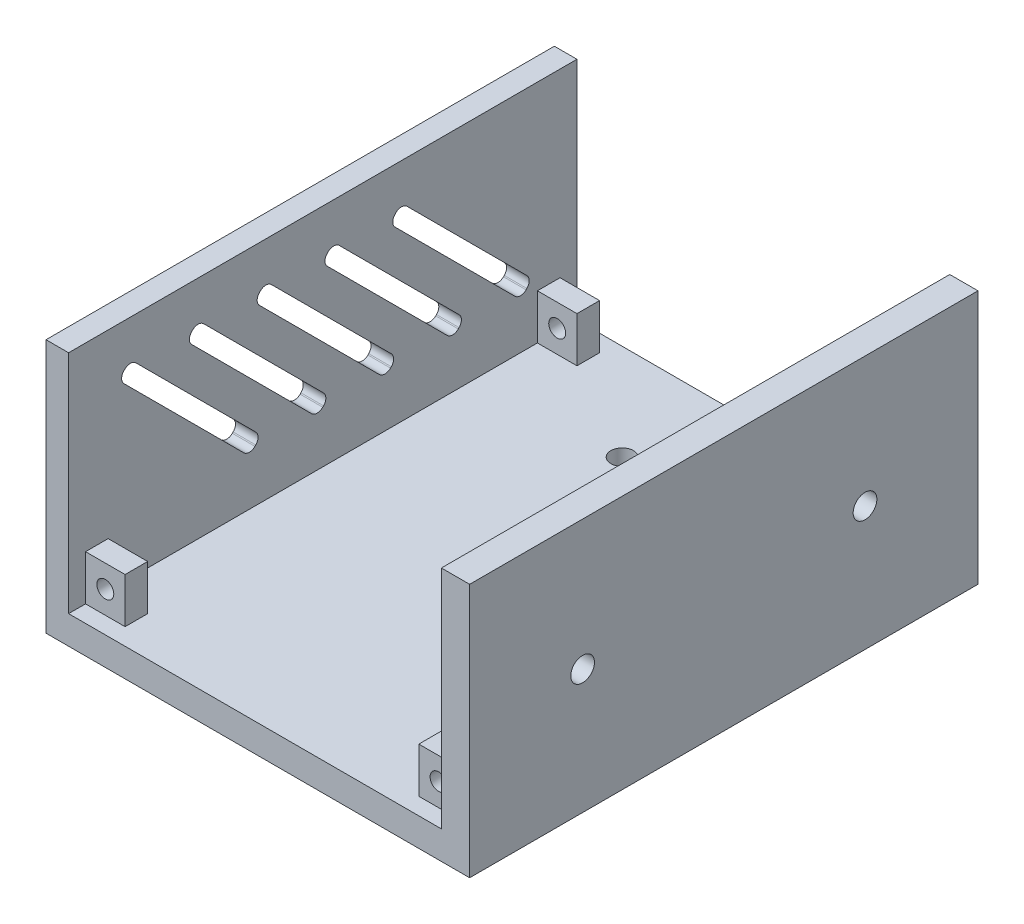
SolidWorks part; units mm, degrees
ref_plane "Front Plane" through (0, 0, 0) normal (0, 0, 1) x (1, 0, 0)
ref_plane "Top Plane" through (0, 0, 0) normal (0, 1, 0) x (1, 0, 0)
ref_plane "Right Plane" through (0, 0, 0) normal (1, 0, 0) x (0, 0, -1)
sketch "Sketch1" plane through (0, 0, 0) normal (0, 0, 1) x (1, 0, 0)
  line L1 (-37.5, -2.5) -> (37.5, -2.5)
  line L2 (-37.5, -2.5) -> (-37.5, 2.5)
  line L3 (-37.5, 2.5) -> (37.5, 2.5)
  line L4 (37.5, -2.5) -> (37.5, 2.5)
  line L5 (-37.5, -2.5) -> (37.5, 2.5) construction
  line L6 (-37.5, 2.5) -> (37.5, -2.5) construction
  line L7 (37.5, 2.5) -> (32.5, 2.5)
  line L8 (37.5, 2.5) -> (37.5, 42.5)
  line L9 (37.5, 42.5) -> (32.5, 42.5)
  line L10 (32.5, 2.5) -> (32.5, 42.5)
  point P0 (0, 0)
  dimension "D1" = 5
  dimension "D2" = 5
  dimension "D3" = 75
  dimension "D4" = 45
extrude "Boss-Extrude1" add sketch "Sketch1" along normal blind 90 contours L1 L4 L3 L2 | L10 L3 L8 L9
sketch "Sketch2" plane through (32.5, 0, 0) normal (-1, 0, 0) x (0, 0, 1)
  line L0 (0, 2.5) -> (0, 42.5) construction
  line L2 (90, 42.5) -> (0, 42.5) construction
  circle A0 centre (20, 19.5) radius 2.1
  circle A1 centre (70, 19.5) radius 2.1
  dimension "D1" = 4.2
  dimension "D2" = 4.2
  dimension "D3" = 20
  dimension "D4" = 50
  dimension "D5" = 23
extrude "Cut-Extrude1" cut sketch "Sketch2" against normal through all
sketch "Sketch4" plane through (0, 2.5, 0) normal (0, 1, 0) x (1, 0, 0)
  line L0 (-37.5, 0) -> (32.5, 0) construction
  line L1 (-37.5, -90) -> (-33.5, -90)
  line L2 (-37.5, -90) -> (-37.5, 0)
  line L3 (-37.5, 0) -> (-33.5, 0)
  line L4 (-33.5, -90) -> (-33.5, 0)
  dimension "D1" = 4
extrude "Boss-Extrude2" add sketch "Sketch4" along normal up to surface (40 mm away) up to face at (35, 42.5, 45)
sketch "Sketch6" plane through (0, 2.5, 0) normal (0, 1, 0) x (1, 0, 0)
  line L0 (-33.5, -90) -> (-33.5, 0) construction
  line L1 (-33.5, -3) -> (-26.5, -3)
  line L2 (-33.5, -3) -> (-33.5, -7)
  line L3 (-33.5, -7) -> (-26.5, -7)
  line L4 (-26.5, -3) -> (-26.5, -7)
  line L5 (-33.5, 0) -> (32.5, 0) construction
  line L6 (-33.5, -45) -> (32.5, -45) construction
  line L7 (32.5, -90) -> (32.5, 0) construction
  line L8 (-0.5, 0) -> (-0.5, -90) construction
  line L9 (-33.5, -90) -> (32.5, -90) construction
  line L10 (25.5, -3) -> (25.5, -7)
  line L11 (32.5, -7) -> (25.5, -7)
  line L12 (32.5, -3) -> (32.5, -7)
  line L13 (32.5, -3) -> (25.5, -3)
  line L14 (32.5, -87) -> (25.5, -87)
  line L15 (32.5, -87) -> (32.5, -83)
  line L16 (32.5, -83) -> (25.5, -83)
  line L17 (25.5, -87) -> (25.5, -83)
  line L18 (-26.5, -87) -> (-26.5, -83)
  line L19 (-33.5, -83) -> (-26.5, -83)
  line L20 (-33.5, -87) -> (-33.5, -83)
  line L21 (-33.5, -87) -> (-26.5, -87)
  dimension "D1" = 3
  dimension "D2" = 4
  dimension "D3" = 7
extrude "Boss-Extrude4" add sketch "Sketch6" along normal blind 8
sketch "Sketch7" plane through (0, 2.5, 0) normal (0, 1, 0) x (1, 0, 0)
  line L0 (-33.5, -90) -> (32.5, -90) construction
  line L1 (32.5, -90) -> (32.5, 0) construction
  circle A0 centre (24.5, -68) radius 1.6
  circle A1 centre (-8.5, -17) radius 1.6
  dimension "D1" = 3.2
  dimension "D4" = 3.2
  dimension "D2" = 51
  dimension "D3" = 33
  dimension "D5" = 22
  dimension "D6" = 8
extrude "Cut-Extrude3" cut sketch "Sketch7" against normal through all
sketch "Sketch8" plane through (-37.5, 0, 0) normal (-1, 0, 0) x (0, 0, 1)
  line L0 (90, -2.5) -> (0, -2.5) construction
  line L1 (32.0613, 34.9899) -> (32.2027, 34.8485)
  line L2 (30.0814, 34.9899) -> (8.8686, 13.7772)
  line L3 (8.8686, 11.7973) -> (9.0101, 11.6559)
  line L4 (32.2027, 32.8686) -> (10.9899, 11.6559)
  line L5 (90, 42.5) -> (0, 42.5) construction
  line L6 (0, -2.5) -> (0, 42.5) construction
  arc A0 (8.8686, 13.7772) -> (8.8686, 11.7973) centre (9.8586, 12.7873) ccw
  arc A1 (9.0101, 11.6559) -> (10.9899, 11.6559) centre (10, 12.6458) ccw
  arc A2 (32.2027, 34.8485) -> (32.2027, 32.8686) centre (31.2127, 33.8586) cw
  arc A3 (32.0613, 34.9899) -> (30.0814, 34.9899) centre (31.0713, 34) ccw
  point P14 (33.1926, 33.8586)
  point P17 (31.0713, 35.9799)
  dimension "D3" = 1.4
  dimension "D1" = 45
  dimension "D2" = 3
  dimension "D4" = 30
  dimension "D5" = 8.5
  dimension "D6" = 10
extrude "Cut-Extrude4" cut sketch "Sketch8" against normal up to next
pattern_linear "LPattern1" count 5 spacing 12 along (0, 0, 1) of "Cut-Extrude4"
sketch "Sketch9" plane through (0, 0, 87) normal (0, 0, 1) x (1, 0, 0)
  line L0 (-26.5, 10.5) -> (-26.5, 2.5) construction
  line L1 (-33.5, 10.5) -> (-26.5, 10.5) construction
  line L3 (25.5, 10.5) -> (25.5, 2.5) construction
  circle A0 centre (-30, 6.5) radius 1.5
  circle A1 centre (29, 6.5) radius 1.5
  dimension "D1" = 3
  dimension "D2" = 3
  dimension "D5" = 3.5
  dimension "D3" = 3.5
  dimension "D4" = 4
extrude "Cut-Extrude5" cut sketch "Sketch9" against normal through all
hole_wizard "CSK for M4 Countersunk Flat Head Screw1" positions "3DSketch1" profile "Sketch10" countersink size "M4" standard "ISO" end condition through all
sketch3d "3DSketch1"
  line L0 (24.5, -2.5, 68) -> (24.5, 2.5, 68) construction
  line L1 (-8.5, -2.5, 17) -> (-8.5, 2.5, 17) construction
  point P0 (24.5, -2.5, 68)
  point P4 (-8.5, -2.5, 17)
sketch "Sketch10" plane through (24.5, -2.5, 68) normal (1, 0, 0) x (0, 0, -1)
  line L0 (0, 0) -> (0, 45)
  line L1 (0, 45) -> (2, 45)
  line L2 (2, 45) -> (2, 1.75)
  line L3 (2, 1.75) -> (3.75, 0)
  line L5 (3.75, 0) -> (0, 0)
  line L6 (-2, 1.75) -> (-3.75, 0) construction
  line L11 (0, -6.35) -> (0, 107.95) construction
  dimension "Thru Hole Dia." = 4
  dimension "Thru Hole Depth" = 45
  dimension "Near C'Sink Dia." = 7.5
  dimension "Near C'Sink Angle" = 90
